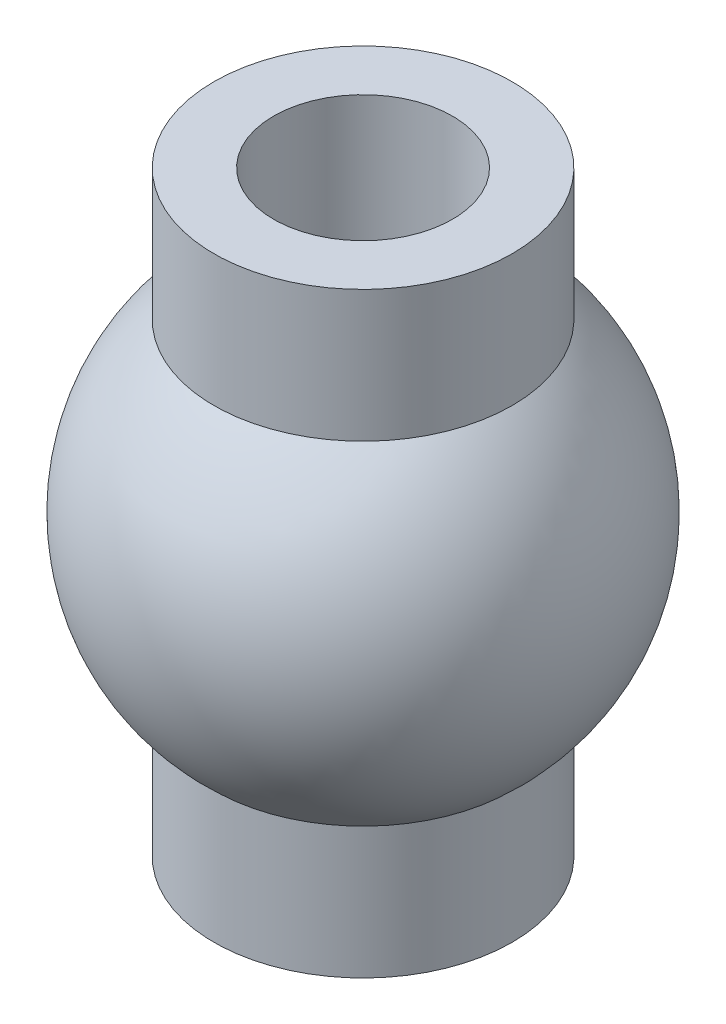
SolidWorks part; units mm, degrees
ref_plane "前视基准面" through (0, 0, 0) normal (0, 0, 1) x (1, 0, 0)
ref_plane "上视基准面" through (0, 0, 0) normal (0, 1, 0) x (1, 0, 0)
ref_plane "右视基准面" through (0, 0, 0) normal (1, 0, 0) x (0, 0, -1)
sketch "草图1" plane through (0, 0, 0) normal (0, 0, 1) x (1, 0, 0)
  line L0 (0, 20) -> (0, 0) construction
  line L1 (0, 20) -> (5, 20)
  line L2 (5, 20) -> (5, 15.5902)
  line L3 (5, 4.4098) -> (5, 0)
  line L4 (5, 0) -> (0, 0)
  line L5 (0, 20) -> (0, 0)
  arc A0 (5, 4.4098) -> (5, 15.5902) centre (0, 10) ccw
  dimension "D1" = 15
  dimension "D2" = 5
  dimension "D3" = 10
  dimension "D4" = 20
revolve "旋转1" add sketch "草图1" angle 360 about L0
sketch "草图2" plane through (0, 20, 0) normal (0, 1, 0) x (1, 0, 0)
  circle A2 centre (0, 0) radius 3
  circle A3 centre (0, 0) radius 3
  dimension "D1" = 2
extrude "切除-拉伸1" cut sketch "草图2" against normal through all
